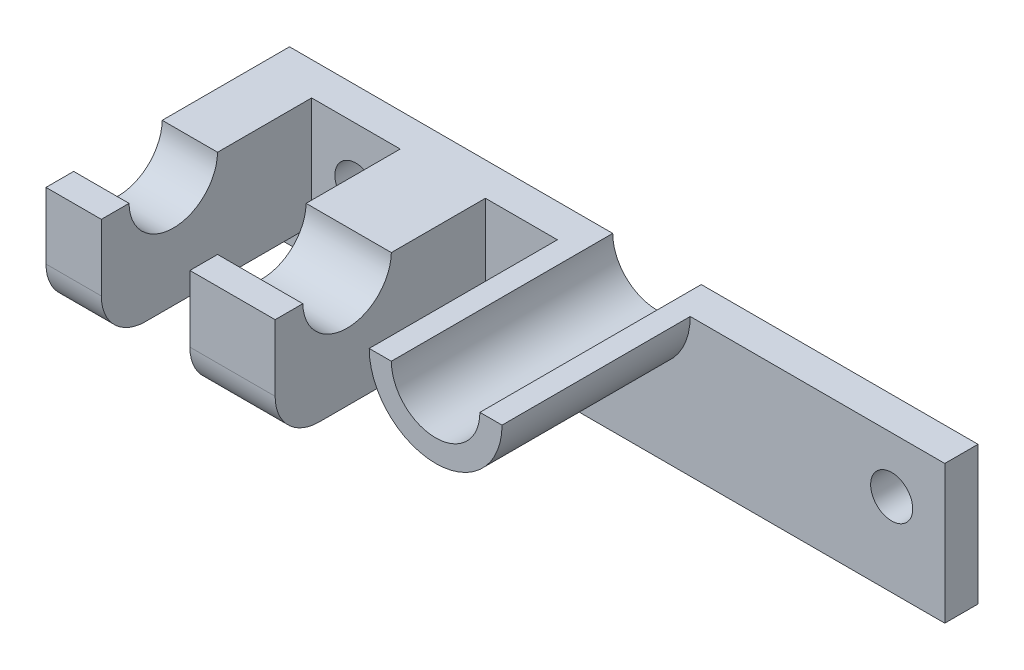
SolidWorks part; units mm, degrees
ref_plane "Front Plane" through (0, 0, 0) normal (0, 0, 1) x (1, 0, 0)
ref_plane "Top Plane" through (0, 0, 0) normal (0, 1, 0) x (1, 0, 0)
ref_plane "Right Plane" through (0, 0, 0) normal (1, 0, 0) x (0, 0, -1)
sketch "Sketch1" plane through (0, 0, 0) normal (0, 0, 1) x (1, 0, 0)
  line L0 (-35.6557, 0) -> (35.5199, 0) construction
  line L1 (-29, 12.5) -> (29, 12.5)
  line L2 (-29, 12.5) -> (-29, -12.5)
  line L3 (-29, -12.5) -> (29, -12.5)
  line L4 (29, 12.5) -> (29, -12.5)
  line L5 (-29, 12.5) -> (29, -12.5) construction
  line L6 (-29, -12.5) -> (29, 12.5) construction
  line L7 (0, 14.8056) -> (0, -17.7939) construction
  circle A0 centre (24.2, 5) radius 1.9
  circle A1 centre (24.2, -5) radius 1.9
  circle A2 centre (-24.2, 5) radius 1.9
  circle A3 centre (-24.2, -5) radius 1.9
  point P0 (0, 0)
  dimension "D3" = 3.8
  dimension "D4" = 3.8
  dimension "D7" = 3.8
  dimension "D8" = 3.8
  dimension "D1" = 58
  dimension "D2" = 25
  dimension "D5" = 10
  dimension "D6" = 5
  dimension "D10" = 24.2
extrude "Boss-Extrude1" add sketch "Sketch1" along normal blind 3
sketch "Sketch2" plane through (0, 0, 0) normal (0, 0, 1) x (1, 0, 0)
  line L0 (-31.697, 0) -> (34.595, 0) construction
  line L1 (0, 15.9391) -> (0, -16.084) construction
  circle A0 centre (0, 0) radius 6
  dimension "D1" = 12
extrude "Boss-Extrude2" add sketch "Sketch2" along normal blind 20
sketch "Sketch3" plane through (0, 0, 20) normal (0, 0, 1) x (1, 0, 0)
  line L0 (0, 15.1421) -> (0, -15.287) construction
  line L1 (-31.4072, 0) -> (31.8419, 0) construction
  circle A0 centre (0, 0) radius 4
  dimension "D1" = 8
extrude "Cut-Extrude1" cut sketch "Sketch3" against normal through all
sketch "Sketch4" plane through (0, 0, 3) normal (0, 0, 1) x (1, 0, 0)
  line L0 (-32.2766, 0) -> (-1.7026, 0) construction
  line L1 (0, 15.8445) -> (0, -16.1506) construction
  line L2 (-20.2, 9.9981) -> (-12.5, 9.9981)
  line L3 (-20.2, 9.9981) -> (-20.2, -9.9981)
  line L4 (-20.2, -9.9981) -> (-12.5, -9.9981)
  line L5 (-12.5, 9.9981) -> (-12.5, -9.9981)
  line L6 (-20.2, 9.9981) -> (-12.5, -9.9981) construction
  line L7 (-20.2, -9.9981) -> (-12.5, 9.9981) construction
  point P3 (-16.35, 0)
  dimension "D1" = 12.5
extrude "Boss-Extrude3" add sketch "Sketch4" along normal blind 19
sketch "Sketch5" plane through (-20.2, 0, 0) normal (-1, 0, 0) x (0, 0, 1)
  line L0 (-1.6546, 0) -> (24.695, 0) construction
  line L1 (15.5, 11.5987) -> (15.5, -11.437) construction
  line L2 (3, 9.9981) -> (3, -9.9981) construction
  circle A0 centre (15.5, 0.0808) radius 4
  dimension "D1" = 8
  dimension "D2" = 12.5
extrude "Cut-Extrude2" cut sketch "Sketch5" against normal up to next
fillet "Fillet1" radius 4 2 edges at (-16.35, -9.9981, 22) (-16.35, 9.9981, 22)
sketch "Sketch7" plane through (0, 0, 3) normal (0, 0, 1) x (1, 0, 0)
  line L0 (-29, -12.5) -> (29, -12.5) construction
  line L1 (-29, 12.5) -> (-33.2, 12.5)
  line L2 (-29, 12.5) -> (-29, -12.5)
  line L3 (-29, -12.5) -> (-33.2, -12.5)
  line L4 (-33.2, 12.5) -> (-33.2, -12.5)
  line L6 (-20.2, 5.9981) -> (-20.2, -5.9981) construction
  dimension "D1" = 13
extrude "Boss-Extrude4" add sketch "Sketch7" against normal blind 3
sketch "Sketch8" plane through (0, 0, 3) normal (0, 0, 1) x (1, 0, 0)
  line L1 (-28.2, 9.9981) -> (-33.2, 9.9981)
  line L2 (-28.2, 9.9981) -> (-28.2, -9.9981)
  line L3 (-28.2, -9.9981) -> (-33.2, -9.9981)
  line L4 (-33.2, 9.9981) -> (-33.2, -9.9981)
  line L5 (-20.2, -9.9981) -> (-12.5, -9.9981) construction
  line L7 (-12.5, 9.9981) -> (-20.2, 9.9981) construction
  dimension "D2" = 5
extrude "Boss-Extrude5" add sketch "Sketch8" along normal blind 19
sketch "Sketch9" plane through (-28.2, 0, 0) normal (1, 0, 0) x (0, 0, -1)
  line L0 (-20.1823, 0) -> (-11.5543, 0) construction
  line L1 (-15.5, 4.3115) -> (-15.5, -4.1843) construction
  circle A0 centre (-15.5, 0.0636) radius 4
  dimension "D1" = 8
extrude "Cut-Extrude3" cut sketch "Sketch9" against normal up to next
fillet "Fillet2" radius 4 2 edges at (-30.7, -9.9981, 22) (-30.7, 9.9981, 22)
sketch "Sketch10" plane through (0, 0, 0) normal (0, 0, -1) x (-1, 0, 0)
  line L0 (-30.183, 0) -> (37.5685, 0) construction
  line L1 (33.2, 12.5) -> (33.2, -12.5) construction
  line L2 (-29, 12.5) -> (33.2, 12.5)
  line L3 (-29, 12.5) -> (-29, 0)
  line L4 (-29, 0) -> (33.2, 0)
  line L5 (33.2, 12.5) -> (33.2, 0)
extrude "Cut-Extrude4" cut sketch "Sketch10" against normal through all
